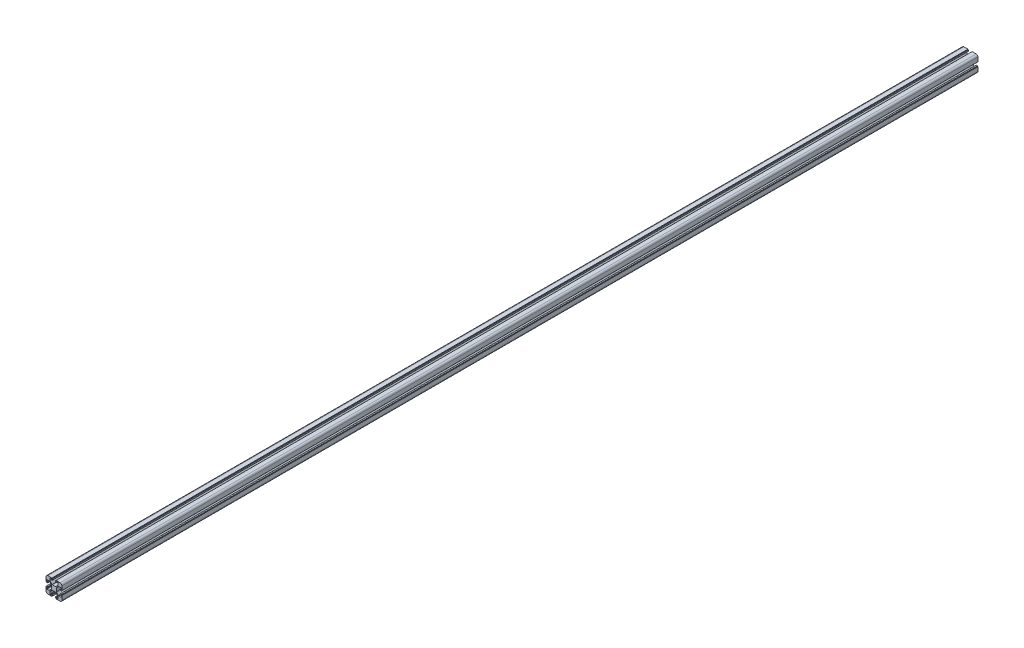
SolidWorks part; units mm, degrees
material "6063-T5"
ref_plane "Front Plane" through (0, 0, 0) normal (0, 0, 1) x (1, 0, 0)
ref_plane "Top Plane" through (0, 0, 0) normal (0, 1, 0) x (1, 0, 0)
ref_plane "Right Plane" through (0, 0, 0) normal (1, 0, 0) x (0, 0, -1)
sketch "Sketch2" plane through (0, 0, 0) normal (0, 0, 1) x (1, 0, 0)
  line L0 (4.5, 0) -> (14.7, 0)
  line L1 (40, 4.5) -> (40, 14.7)
  line L2 (35.5, 40) -> (25.3, 40)
  line L3 (0, 35.5) -> (0, 25.3)
  line L4 (15.9, 1.2) -> (15.9, 4.2)
  line L5 (24.1, 1.2) -> (24.1, 4.2)
  line L6 (38.8, 24.1) -> (35.8, 24.1)
  line L7 (35.5, 24.4) -> (35.5, 26.1)
  line L8 (14, 23.7574) -> (14, 16.2426)
  line L9 (16.2426, 14) -> (23.7574, 14)
  line L10 (26, 16.2426) -> (26, 23.7574)
  line L11 (13.4142, 14.8284) -> (8.9216, 10.3358)
  line L12 (23.7574, 26) -> (16.2426, 26)
  line L13 (4.5, 24.4) -> (4.5, 26.1)
  line L14 (1.2, 24.1) -> (4.2, 24.1)
  line L15 (15.9, 38.8) -> (15.9, 35.8)
  line L16 (14.8284, 26.5858) -> (10.3358, 31.0784)
  line L17 (13.4142, 25.1716) -> (8.9216, 29.6642)
  line L18 (14.8284, 13.4142) -> (10.3358, 8.9216)
  line L19 (25.1716, 13.4142) -> (29.6642, 8.9216)
  line L20 (26.5858, 14.8284) -> (31.0784, 10.3358)
  line L21 (26.5858, 25.1716) -> (31.0784, 29.6642)
  line L22 (25.1716, 26.5858) -> (29.6642, 31.0784)
  line L23 (24.1, 38.8) -> (24.1, 35.8)
  line L24 (14.7, 40) -> (4.5, 40)
  line L25 (25.3, 0) -> (35.5, 0)
  line L26 (38.8, 15.9) -> (35.8, 15.9)
  line L27 (40, 25.3) -> (40, 35.5)
  line L28 (1.2, 15.9) -> (4.2, 15.9)
  line L29 (0, 14.7) -> (0, 4.5)
  line L30 (4.5, 15.6) -> (4.5, 13.9)
  line L31 (35.5, 15.6) -> (35.5, 13.9)
  line L32 (15.6, 35.5) -> (13.9, 35.5)
  line L33 (24.4, 35.5) -> (26.1, 35.5)
  line L34 (15.6, 4.5) -> (13.9, 4.5)
  line L35 (24.4, 4.5) -> (26.1, 4.5)
  line L36 (12.6, 38.5) -> (10.75, 38.5)
  line L37 (1.5, 12.6) -> (1.5, 10.75)
  line L38 (27.4, 1.5) -> (29.25, 1.5)
  line L39 (38.5, 27.4) -> (38.5, 29.25)
  line L40 (38.5, 10.75) -> (38.5, 12.6)
  line L41 (29.25, 38.5) -> (27.4, 38.5)
  line L42 (1.5, 29.25) -> (1.5, 27.4)
  line L43 (10.75, 1.5) -> (12.6, 1.5)
  line L44 (35.8, 26.4) -> (37.5, 26.4)
  line L45 (35.8, 13.6) -> (37.5, 13.6)
  line L46 (4.2, 26.4) -> (2.5, 26.4)
  line L47 (13.6, 35.8) -> (13.6, 37.5)
  line L48 (26.4, 35.8) -> (26.4, 37.5)
  line L49 (4.2, 13.6) -> (2.5, 13.6)
  line L50 (13.6, 4.2) -> (13.6, 2.5)
  line L51 (26.4, 4.2) -> (26.4, 2.5)
  line L52 (9.75, 7.5074) -> (9.75, 2.5)
  line L53 (30.25, 7.5074) -> (30.25, 2.5)
  line L54 (9.75, 37.5) -> (9.75, 32.4926)
  line L55 (30.25, 37.5) -> (30.25, 32.4926)
  line L56 (32.4926, 30.25) -> (37.5, 30.25)
  line L57 (37.5, 9.75) -> (32.4926, 9.75)
  line L58 (2.5, 30.25) -> (7.5074, 30.25)
  line L59 (2.5, 9.75) -> (7.5074, 9.75)
  line L60 (31.55, 37.7) -> (31.55, 32.55)
  line L61 (32.55, 31.55) -> (37.7, 31.55)
  line L62 (1.3, 35.5) -> (1.3, 32.55)
  line L63 (4.5, 38.7) -> (7.45, 38.7)
  line L64 (32.55, 38.7) -> (35.5, 38.7)
  line L65 (38.7, 35.5) -> (38.7, 32.55)
  line L66 (8.45, 37.7) -> (8.45, 32.55)
  line L67 (2.3, 31.55) -> (7.45, 31.55)
  line L68 (1.3, 7.45) -> (1.3, 4.5)
  line L69 (2.3, 8.45) -> (7.45, 8.45)
  line L70 (8.45, 7.45) -> (8.45, 2.3)
  line L71 (4.5, 1.3) -> (7.45, 1.3)
  line L72 (31.55, 7.45) -> (31.55, 2.3)
  line L73 (32.55, 8.45) -> (37.7, 8.45)
  line L74 (38.7, 7.45) -> (38.7, 4.5)
  line L75 (32.55, 1.3) -> (35.5, 1.3)
  line L77 (14.9, 39.8) -> (14.9, 39.2)
  line L78 (15.1, 39) -> (15.7, 39)
  line L79 (25.1, 39.8) -> (25.1, 39.2)
  line L80 (24.9, 39) -> (24.3, 39)
  line L81 (25.1, 0.2) -> (25.1, 0.8)
  line L82 (24.9, 1) -> (24.3, 1)
  line L83 (14.9, 0.2) -> (14.9, 0.8)
  line L84 (15.1, 1) -> (15.7, 1)
  line L85 (0.2, 25.1) -> (0.8, 25.1)
  line L86 (1, 24.9) -> (1, 24.3)
  line L87 (0.2, 14.9) -> (0.8, 14.9)
  line L88 (1, 15.1) -> (1, 15.7)
  line L89 (39.8, 25.1) -> (39.2, 25.1)
  line L90 (39, 24.9) -> (39, 24.3)
  line L91 (39, 15.7) -> (39, 15.1)
  line L92 (39.2, 14.9) -> (39.8, 14.9)
  circle A0 centre (20, 20) radius 3.4
  arc A1 (1.3, 35.5) -> (4.5, 38.7) centre (4.5, 35.5) cw
  arc A2 (1.3, 4.5) -> (4.5, 1.3) centre (4.5, 4.5) ccw
  arc A3 (38.7, 4.5) -> (35.5, 1.3) centre (35.5, 4.5) cw
  arc A4 (35.5, 38.7) -> (38.7, 35.5) centre (35.5, 35.5) cw
  arc A5 (40, 35.5) -> (35.5, 40) centre (35.5, 35.5) ccw
  arc A6 (35.5, 0) -> (40, 4.5) centre (35.5, 4.5) ccw
  arc A7 (4.5, 0) -> (0, 4.5) centre (4.5, 4.5) cw
  arc A8 (4.5, 40) -> (0, 35.5) centre (4.5, 35.5) ccw
  arc A9 (13.4142, 14.8284) -> (14, 16.2426) centre (12, 16.2426) ccw
  arc A10 (7.5074, 9.75) -> (8.9216, 10.3358) centre (7.5074, 11.75) ccw
  arc A11 (9.75, 7.5074) -> (10.3358, 8.9216) centre (11.75, 7.5074) cw
  arc A12 (30.25, 7.5074) -> (29.6642, 8.9216) centre (28.25, 7.5074) ccw
  arc A13 (14.8284, 13.4142) -> (16.2426, 14) centre (16.2426, 12) cw
  arc A14 (25.1716, 13.4142) -> (23.7574, 14) centre (23.7574, 12) ccw
  arc A15 (32.4926, 9.75) -> (31.0784, 10.3358) centre (32.4926, 11.75) cw
  arc A16 (26.5858, 14.8284) -> (26, 16.2426) centre (28, 16.2426) cw
  arc A17 (32.4926, 30.25) -> (31.0784, 29.6642) centre (32.4926, 28.25) ccw
  arc A18 (26.5858, 25.1716) -> (26, 23.7574) centre (28, 23.7574) ccw
  arc A19 (13.4142, 25.1716) -> (14, 23.7574) centre (12, 23.7574) cw
  arc A20 (7.5074, 30.25) -> (8.9216, 29.6642) centre (7.5074, 28.25) cw
  arc A21 (9.75, 32.4926) -> (10.3358, 31.0784) centre (11.75, 32.4926) ccw
  arc A22 (30.25, 32.4926) -> (29.6642, 31.0784) centre (28.25, 32.4926) cw
  arc A23 (25.1716, 26.5858) -> (23.7574, 26) centre (23.7574, 28) cw
  arc A24 (14.8284, 26.5858) -> (16.2426, 26) centre (16.2426, 28) ccw
  arc A25 (37.7, 8.45) -> (38.7, 7.45) centre (37.7, 7.45) cw
  arc A26 (31.55, 2.3) -> (32.55, 1.3) centre (32.55, 2.3) ccw
  arc A27 (31.55, 7.45) -> (32.55, 8.45) centre (32.55, 7.45) cw
  arc A28 (8.45, 2.3) -> (7.45, 1.3) centre (7.45, 2.3) cw
  arc A29 (1.3, 7.45) -> (2.3, 8.45) centre (2.3, 7.45) cw
  arc A30 (7.45, 8.45) -> (8.45, 7.45) centre (7.45, 7.45) cw
  arc A31 (38.7, 32.55) -> (37.7, 31.55) centre (37.7, 32.55) cw
  arc A32 (31.55, 32.55) -> (32.55, 31.55) centre (32.55, 32.55) ccw
  arc A33 (31.55, 37.7) -> (32.55, 38.7) centre (32.55, 37.7) cw
  arc A34 (7.45, 38.7) -> (8.45, 37.7) centre (7.45, 37.7) cw
  arc A35 (8.45, 32.55) -> (7.45, 31.55) centre (7.45, 32.55) cw
  arc A36 (1.3, 32.55) -> (2.3, 31.55) centre (2.3, 32.55) ccw
  arc A37 (30.25, 2.5) -> (29.25, 1.5) centre (29.25, 2.5) cw
  arc A38 (26.4, 2.5) -> (27.4, 1.5) centre (27.4, 2.5) ccw
  arc A39 (13.6, 2.5) -> (12.6, 1.5) centre (12.6, 2.5) cw
  arc A40 (9.75, 2.5) -> (10.75, 1.5) centre (10.75, 2.5) ccw
  arc A41 (26.4, 37.5) -> (27.4, 38.5) centre (27.4, 37.5) cw
  arc A42 (30.25, 37.5) -> (29.25, 38.5) centre (29.25, 37.5) ccw
  arc A43 (37.5, 26.4) -> (38.5, 27.4) centre (37.5, 27.4) ccw
  arc A44 (37.5, 30.25) -> (38.5, 29.25) centre (37.5, 29.25) cw
  arc A45 (37.5, 13.6) -> (38.5, 12.6) centre (37.5, 12.6) cw
  arc A46 (37.5, 9.75) -> (38.5, 10.75) centre (37.5, 10.75) ccw
  arc A47 (2.5, 9.75) -> (1.5, 10.75) centre (2.5, 10.75) cw
  arc A48 (2.5, 13.6) -> (1.5, 12.6) centre (2.5, 12.6) ccw
  arc A49 (2.5, 26.4) -> (1.5, 27.4) centre (2.5, 27.4) cw
  arc A50 (2.5, 30.25) -> (1.5, 29.25) centre (2.5, 29.25) ccw
  arc A51 (9.75, 37.5) -> (10.75, 38.5) centre (10.75, 37.5) cw
  arc A52 (13.6, 37.5) -> (12.6, 38.5) centre (12.6, 37.5) ccw
  arc A53 (26.1, 35.5) -> (26.4, 35.8) centre (26.1, 35.8) ccw
  arc A54 (24.1, 35.8) -> (24.4, 35.5) centre (24.4, 35.8) ccw
  arc A55 (15.9, 35.8) -> (15.6, 35.5) centre (15.6, 35.8) cw
  arc A56 (13.9, 35.5) -> (13.6, 35.8) centre (13.9, 35.8) cw
  arc A57 (13.9, 4.5) -> (13.6, 4.2) centre (13.9, 4.2) ccw
  arc A58 (15.9, 4.2) -> (15.6, 4.5) centre (15.6, 4.2) ccw
  arc A59 (24.1, 4.2) -> (24.4, 4.5) centre (24.4, 4.2) cw
  arc A60 (26.1, 4.5) -> (26.4, 4.2) centre (26.1, 4.2) cw
  arc A61 (35.5, 13.9) -> (35.8, 13.6) centre (35.8, 13.9) ccw
  arc A62 (35.8, 15.9) -> (35.5, 15.6) centre (35.8, 15.6) ccw
  arc A63 (35.8, 24.1) -> (35.5, 24.4) centre (35.8, 24.4) cw
  arc A64 (35.5, 26.1) -> (35.8, 26.4) centre (35.8, 26.1) cw
  arc A65 (4.5, 13.9) -> (4.2, 13.6) centre (4.2, 13.9) cw
  arc A66 (4.2, 15.9) -> (4.5, 15.6) centre (4.2, 15.6) cw
  arc A67 (4.2, 24.1) -> (4.5, 24.4) centre (4.2, 24.4) ccw
  arc A68 (4.5, 26.1) -> (4.2, 26.4) centre (4.2, 26.1) ccw
  arc A69 (25.3, 0) -> (25.1, 0.2) centre (25.3, 0.2) cw
  arc A70 (25.1, 0.8) -> (24.9, 1) centre (24.9, 0.8) ccw
  arc A71 (24.3, 1) -> (24.1, 1.2) centre (24.3, 1.2) cw
  arc A72 (14.7, 0) -> (14.9, 0.2) centre (14.7, 0.2) ccw
  arc A73 (14.9, 0.8) -> (15.1, 1) centre (15.1, 0.8) cw
  arc A74 (15.7, 1) -> (15.9, 1.2) centre (15.7, 1.2) ccw
  arc A75 (39.8, 14.9) -> (40, 14.7) centre (39.8, 14.7) cw
  arc A76 (39, 15.1) -> (39.2, 14.9) centre (39.2, 15.1) ccw
  arc A77 (38.8, 15.9) -> (39, 15.7) centre (38.8, 15.7) cw
  arc A78 (0, 25.3) -> (0.2, 25.1) centre (0.2, 25.3) ccw
  arc A79 (0.8, 25.1) -> (1, 24.9) centre (0.8, 24.9) cw
  arc A80 (1, 24.3) -> (1.2, 24.1) centre (1.2, 24.3) ccw
  arc A81 (0, 14.7) -> (0.2, 14.9) centre (0.2, 14.7) cw
  arc A82 (0.8, 14.9) -> (1, 15.1) centre (0.8, 15.1) ccw
  arc A83 (1, 15.7) -> (1.2, 15.9) centre (1.2, 15.7) cw
  arc A84 (39, 24.3) -> (38.8, 24.1) centre (38.8, 24.3) cw
  arc A85 (39.2, 25.1) -> (39, 24.9) centre (39.2, 24.9) ccw
  arc A86 (40, 25.3) -> (39.8, 25.1) centre (39.8, 25.3) cw
  arc A87 (24.3, 39) -> (24.1, 38.8) centre (24.3, 38.8) ccw
  arc A88 (25.1, 39.2) -> (24.9, 39) centre (24.9, 39.2) cw
  arc A89 (25.3, 40) -> (25.1, 39.8) centre (25.3, 39.8) ccw
  arc A90 (14.9, 39.2) -> (15.1, 39) centre (15.1, 39.2) ccw
  arc A91 (15.7, 39) -> (15.9, 38.8) centre (15.7, 38.8) cw
  arc A92 (14.7, 40) -> (14.9, 39.8) centre (14.7, 39.8) cw
  point P93 (0, 0)
extrude "Boss-Extrude1" add sketch "Sketch2" along normal blind 50
sketch "Sketch3" plane through (0, 0, 50) normal (0, 0, 1) x (1, 0, 0)
  line L76 (25.3, 0) -> (35.5, 0)
  line L77 (40, 4.5) -> (40, 14.7)
  line L78 (39.8, 14.9) -> (39.2, 14.9)
  line L79 (39, 15.1) -> (39, 15.7)
  line L80 (38.8, 15.9) -> (35.8, 15.9)
  line L81 (35.5, 15.6) -> (35.5, 13.9)
  line L82 (35.8, 13.6) -> (37.5, 13.6)
  line L83 (38.5, 12.6) -> (38.5, 10.75)
  line L84 (37.5, 9.75) -> (32.4926, 9.75)
  line L85 (31.0784, 10.3358) -> (26.5858, 14.8284)
  line L86 (26, 16.2426) -> (26, 23.7574)
  line L87 (26.5858, 25.1716) -> (31.0784, 29.6642)
  line L88 (32.4926, 30.25) -> (37.5, 30.25)
  line L89 (38.5, 29.25) -> (38.5, 27.4)
  line L90 (37.5, 26.4) -> (35.8, 26.4)
  line L91 (35.5, 26.1) -> (35.5, 24.4)
  line L92 (35.8, 24.1) -> (38.8, 24.1)
  line L93 (39, 24.3) -> (39, 24.9)
  line L94 (39.2, 25.1) -> (39.8, 25.1)
  line L95 (40, 25.3) -> (40, 35.5)
  line L96 (35.5, 40) -> (25.3, 40)
  line L97 (25.1, 39.8) -> (25.1, 39.2)
  line L98 (24.9, 39) -> (24.3, 39)
  line L99 (24.1, 38.8) -> (24.1, 35.8)
  line L100 (24.4, 35.5) -> (26.1, 35.5)
  line L101 (26.4, 35.8) -> (26.4, 37.5)
  line L102 (27.4, 38.5) -> (29.25, 38.5)
  line L103 (30.25, 37.5) -> (30.25, 32.4926)
  line L104 (29.6642, 31.0784) -> (25.1716, 26.5858)
  line L105 (23.7574, 26) -> (16.2426, 26)
  line L106 (14.8284, 26.5858) -> (10.3358, 31.0784)
  line L107 (9.75, 32.4926) -> (9.75, 37.5)
  line L108 (10.75, 38.5) -> (12.6, 38.5)
  line L109 (13.6, 37.5) -> (13.6, 35.8)
  line L110 (13.9, 35.5) -> (15.6, 35.5)
  line L111 (15.9, 35.8) -> (15.9, 38.8)
  line L112 (15.7, 39) -> (15.1, 39)
  line L113 (14.9, 39.2) -> (14.9, 39.8)
  line L114 (14.7, 40) -> (4.5, 40)
  line L115 (0, 35.5) -> (0, 25.3)
  line L116 (0.2, 25.1) -> (0.8, 25.1)
  line L117 (1, 24.9) -> (1, 24.3)
  line L118 (1.2, 24.1) -> (4.2, 24.1)
  line L119 (4.5, 24.4) -> (4.5, 26.1)
  line L120 (4.2, 26.4) -> (2.5, 26.4)
  line L121 (1.5, 27.4) -> (1.5, 29.25)
  line L122 (2.5, 30.25) -> (7.5074, 30.25)
  line L123 (8.9216, 29.6642) -> (13.4142, 25.1716)
  line L124 (14, 23.7574) -> (14, 16.2426)
  line L125 (13.4142, 14.8284) -> (8.9216, 10.3358)
  line L126 (7.5074, 9.75) -> (2.5, 9.75)
  line L127 (1.5, 10.75) -> (1.5, 12.6)
  line L128 (2.5, 13.6) -> (4.2, 13.6)
  line L129 (4.5, 13.9) -> (4.5, 15.6)
  line L130 (4.2, 15.9) -> (1.2, 15.9)
  line L131 (1, 15.7) -> (1, 15.1)
  line L132 (0.8, 14.9) -> (0.2, 14.9)
  line L133 (0, 14.7) -> (0, 4.5)
  line L134 (4.5, 0) -> (14.7, 0)
  line L135 (14.9, 0.2) -> (14.9, 0.8)
  line L136 (15.1, 1) -> (15.7, 1)
  line L137 (15.9, 1.2) -> (15.9, 4.2)
  line L138 (15.6, 4.5) -> (13.9, 4.5)
  line L139 (13.6, 4.2) -> (13.6, 2.5)
  line L140 (12.6, 1.5) -> (10.75, 1.5)
  line L141 (9.75, 2.5) -> (9.75, 7.5074)
  line L142 (10.3358, 8.9216) -> (14.8284, 13.4142)
  line L143 (16.2426, 14) -> (23.7574, 14)
  line L144 (25.1716, 13.4142) -> (29.6642, 8.9216)
  line L145 (30.25, 7.5074) -> (30.25, 2.5)
  line L146 (29.25, 1.5) -> (27.4, 1.5)
  line L147 (26.4, 2.5) -> (26.4, 4.2)
  line L148 (26.1, 4.5) -> (24.4, 4.5)
  line L149 (24.1, 4.2) -> (24.1, 1.2)
  line L150 (24.3, 1) -> (24.9, 1)
  line L151 (25.1, 0.8) -> (25.1, 0.2)
  line L152 (25.3, 0) -> (35.5, 0)
  line L153 (40, 4.5) -> (40, 14.7)
  line L154 (39.8, 14.9) -> (39.2, 14.9)
  line L155 (39, 15.1) -> (39, 15.7)
  line L156 (38.8, 15.9) -> (35.8, 15.9)
  line L157 (35.5, 15.6) -> (35.5, 13.9)
  line L158 (35.8, 13.6) -> (37.5, 13.6)
  line L159 (38.5, 12.6) -> (38.5, 10.75)
  line L160 (37.5, 9.75) -> (32.4926, 9.75)
  line L161 (31.0784, 10.3358) -> (26.5858, 14.8284)
  line L162 (26, 16.2426) -> (26, 23.7574)
  line L163 (26.5858, 25.1716) -> (31.0784, 29.6642)
  line L164 (32.4926, 30.25) -> (37.5, 30.25)
  line L165 (38.5, 29.25) -> (38.5, 27.4)
  line L166 (37.5, 26.4) -> (35.8, 26.4)
  line L167 (35.5, 26.1) -> (35.5, 24.4)
  line L168 (35.8, 24.1) -> (38.8, 24.1)
  line L169 (39, 24.3) -> (39, 24.9)
  line L170 (39.2, 25.1) -> (39.8, 25.1)
  line L171 (40, 25.3) -> (40, 35.5)
  line L172 (35.5, 40) -> (25.3, 40)
  line L173 (25.1, 39.8) -> (25.1, 39.2)
  line L174 (24.9, 39) -> (24.3, 39)
  line L175 (24.1, 38.8) -> (24.1, 35.8)
  line L176 (24.4, 35.5) -> (26.1, 35.5)
  line L177 (26.4, 35.8) -> (26.4, 37.5)
  line L178 (27.4, 38.5) -> (29.25, 38.5)
  line L179 (30.25, 37.5) -> (30.25, 32.4926)
  line L180 (29.6642, 31.0784) -> (25.1716, 26.5858)
  line L181 (23.7574, 26) -> (16.2426, 26)
  line L182 (14.8284, 26.5858) -> (10.3358, 31.0784)
  line L183 (9.75, 32.4926) -> (9.75, 37.5)
  line L184 (10.75, 38.5) -> (12.6, 38.5)
  line L185 (13.6, 37.5) -> (13.6, 35.8)
  line L186 (13.9, 35.5) -> (15.6, 35.5)
  line L187 (15.9, 35.8) -> (15.9, 38.8)
  line L188 (15.7, 39) -> (15.1, 39)
  line L189 (14.9, 39.2) -> (14.9, 39.8)
  line L190 (14.7, 40) -> (4.5, 40)
  line L191 (0, 35.5) -> (0, 25.3)
  line L192 (0.2, 25.1) -> (0.8, 25.1)
  line L193 (1, 24.9) -> (1, 24.3)
  line L194 (1.2, 24.1) -> (4.2, 24.1)
  line L195 (4.5, 24.4) -> (4.5, 26.1)
  line L196 (4.2, 26.4) -> (2.5, 26.4)
  line L197 (1.5, 27.4) -> (1.5, 29.25)
  line L198 (2.5, 30.25) -> (7.5074, 30.25)
  line L199 (8.9216, 29.6642) -> (13.4142, 25.1716)
  line L200 (14, 23.7574) -> (14, 16.2426)
  line L201 (13.4142, 14.8284) -> (8.9216, 10.3358)
  line L202 (7.5074, 9.75) -> (2.5, 9.75)
  line L203 (1.5, 10.75) -> (1.5, 12.6)
  line L204 (2.5, 13.6) -> (4.2, 13.6)
  line L205 (4.5, 13.9) -> (4.5, 15.6)
  line L206 (4.2, 15.9) -> (1.2, 15.9)
  line L207 (1, 15.7) -> (1, 15.1)
  line L208 (0.8, 14.9) -> (0.2, 14.9)
  line L209 (0, 14.7) -> (0, 4.5)
  line L210 (4.5, 0) -> (14.7, 0)
  line L211 (14.9, 0.2) -> (14.9, 0.8)
  line L212 (15.1, 1) -> (15.7, 1)
  line L213 (15.9, 1.2) -> (15.9, 4.2)
  line L214 (15.6, 4.5) -> (13.9, 4.5)
  line L215 (13.6, 4.2) -> (13.6, 2.5)
  line L216 (12.6, 1.5) -> (10.75, 1.5)
  line L217 (9.75, 2.5) -> (9.75, 7.5074)
  line L218 (10.3358, 8.9216) -> (14.8284, 13.4142)
  line L219 (16.2426, 14) -> (23.7574, 14)
  line L220 (25.1716, 13.4142) -> (29.6642, 8.9216)
  line L221 (30.25, 7.5074) -> (30.25, 2.5)
  line L222 (29.25, 1.5) -> (27.4, 1.5)
  line L223 (26.4, 2.5) -> (26.4, 4.2)
  line L224 (26.1, 4.5) -> (24.4, 4.5)
  line L225 (24.1, 4.2) -> (24.1, 1.2)
  line L226 (24.3, 1) -> (24.9, 1)
  line L227 (25.1, 0.8) -> (25.1, 0.2)
  arc A76 (25.1, 0.2) -> (25.3, 0) centre (25.3, 0.2) ccw
  arc A77 (35.5, 0) -> (40, 4.5) centre (35.5, 4.5) ccw
  arc A78 (40, 14.7) -> (39.8, 14.9) centre (39.8, 14.7) ccw
  arc A79 (39, 15.1) -> (39.2, 14.9) centre (39.2, 15.1) ccw
  arc A80 (39, 15.7) -> (38.8, 15.9) centre (38.8, 15.7) ccw
  arc A81 (35.8, 15.9) -> (35.5, 15.6) centre (35.8, 15.6) ccw
  arc A82 (35.5, 13.9) -> (35.8, 13.6) centre (35.8, 13.9) ccw
  arc A83 (38.5, 12.6) -> (37.5, 13.6) centre (37.5, 12.6) ccw
  arc A84 (37.5, 9.75) -> (38.5, 10.75) centre (37.5, 10.75) ccw
  arc A85 (31.0784, 10.3358) -> (32.4926, 9.75) centre (32.4926, 11.75) ccw
  arc A86 (26, 16.2426) -> (26.5858, 14.8284) centre (28, 16.2426) ccw
  arc A87 (26.5858, 25.1716) -> (26, 23.7574) centre (28, 23.7574) ccw
  arc A88 (32.4926, 30.25) -> (31.0784, 29.6642) centre (32.4926, 28.25) ccw
  arc A89 (38.5, 29.25) -> (37.5, 30.25) centre (37.5, 29.25) ccw
  arc A90 (37.5, 26.4) -> (38.5, 27.4) centre (37.5, 27.4) ccw
  arc A91 (35.8, 26.4) -> (35.5, 26.1) centre (35.8, 26.1) ccw
  arc A92 (35.5, 24.4) -> (35.8, 24.1) centre (35.8, 24.4) ccw
  arc A93 (38.8, 24.1) -> (39, 24.3) centre (38.8, 24.3) ccw
  arc A94 (39.2, 25.1) -> (39, 24.9) centre (39.2, 24.9) ccw
  arc A95 (39.8, 25.1) -> (40, 25.3) centre (39.8, 25.3) ccw
  arc A96 (40, 35.5) -> (35.5, 40) centre (35.5, 35.5) ccw
  arc A97 (25.3, 40) -> (25.1, 39.8) centre (25.3, 39.8) ccw
  arc A98 (24.9, 39) -> (25.1, 39.2) centre (24.9, 39.2) ccw
  arc A99 (24.3, 39) -> (24.1, 38.8) centre (24.3, 38.8) ccw
  arc A100 (24.1, 35.8) -> (24.4, 35.5) centre (24.4, 35.8) ccw
  arc A101 (26.1, 35.5) -> (26.4, 35.8) centre (26.1, 35.8) ccw
  arc A102 (27.4, 38.5) -> (26.4, 37.5) centre (27.4, 37.5) ccw
  arc A103 (30.25, 37.5) -> (29.25, 38.5) centre (29.25, 37.5) ccw
  arc A104 (29.6642, 31.0784) -> (30.25, 32.4926) centre (28.25, 32.4926) ccw
  arc A105 (23.7574, 26) -> (25.1716, 26.5858) centre (23.7574, 28) ccw
  arc A106 (14.8284, 26.5858) -> (16.2426, 26) centre (16.2426, 28) ccw
  arc A107 (9.75, 32.4926) -> (10.3358, 31.0784) centre (11.75, 32.4926) ccw
  arc A108 (10.75, 38.5) -> (9.75, 37.5) centre (10.75, 37.5) ccw
  arc A109 (13.6, 37.5) -> (12.6, 38.5) centre (12.6, 37.5) ccw
  arc A110 (13.6, 35.8) -> (13.9, 35.5) centre (13.9, 35.8) ccw
  arc A111 (15.6, 35.5) -> (15.9, 35.8) centre (15.6, 35.8) ccw
  arc A112 (15.9, 38.8) -> (15.7, 39) centre (15.7, 38.8) ccw
  arc A113 (14.9, 39.2) -> (15.1, 39) centre (15.1, 39.2) ccw
  arc A114 (14.9, 39.8) -> (14.7, 40) centre (14.7, 39.8) ccw
  arc A115 (4.5, 40) -> (0, 35.5) centre (4.5, 35.5) ccw
  arc A116 (0, 25.3) -> (0.2, 25.1) centre (0.2, 25.3) ccw
  arc A117 (1, 24.9) -> (0.8, 25.1) centre (0.8, 24.9) ccw
  arc A118 (1, 24.3) -> (1.2, 24.1) centre (1.2, 24.3) ccw
  arc A119 (4.2, 24.1) -> (4.5, 24.4) centre (4.2, 24.4) ccw
  arc A120 (4.5, 26.1) -> (4.2, 26.4) centre (4.2, 26.1) ccw
  arc A121 (1.5, 27.4) -> (2.5, 26.4) centre (2.5, 27.4) ccw
  arc A122 (2.5, 30.25) -> (1.5, 29.25) centre (2.5, 29.25) ccw
  arc A123 (8.9216, 29.6642) -> (7.5074, 30.25) centre (7.5074, 28.25) ccw
  arc A124 (14, 23.7574) -> (13.4142, 25.1716) centre (12, 23.7574) ccw
  arc A125 (13.4142, 14.8284) -> (14, 16.2426) centre (12, 16.2426) ccw
  arc A126 (7.5074, 9.75) -> (8.9216, 10.3358) centre (7.5074, 11.75) ccw
  arc A127 (1.5, 10.75) -> (2.5, 9.75) centre (2.5, 10.75) ccw
  arc A128 (2.5, 13.6) -> (1.5, 12.6) centre (2.5, 12.6) ccw
  arc A129 (4.2, 13.6) -> (4.5, 13.9) centre (4.2, 13.9) ccw
  arc A130 (4.5, 15.6) -> (4.2, 15.9) centre (4.2, 15.6) ccw
  arc A131 (1.2, 15.9) -> (1, 15.7) centre (1.2, 15.7) ccw
  arc A132 (0.8, 14.9) -> (1, 15.1) centre (0.8, 15.1) ccw
  arc A133 (0.2, 14.9) -> (0, 14.7) centre (0.2, 14.7) ccw
  arc A134 (0, 4.5) -> (4.5, 0) centre (4.5, 4.5) ccw
  arc A135 (14.7, 0) -> (14.9, 0.2) centre (14.7, 0.2) ccw
  arc A136 (15.1, 1) -> (14.9, 0.8) centre (15.1, 0.8) ccw
  arc A137 (15.7, 1) -> (15.9, 1.2) centre (15.7, 1.2) ccw
  arc A138 (15.9, 4.2) -> (15.6, 4.5) centre (15.6, 4.2) ccw
  arc A139 (13.9, 4.5) -> (13.6, 4.2) centre (13.9, 4.2) ccw
  arc A140 (12.6, 1.5) -> (13.6, 2.5) centre (12.6, 2.5) ccw
  arc A141 (9.75, 2.5) -> (10.75, 1.5) centre (10.75, 2.5) ccw
  arc A142 (10.3358, 8.9216) -> (9.75, 7.5074) centre (11.75, 7.5074) ccw
  arc A143 (16.2426, 14) -> (14.8284, 13.4142) centre (16.2426, 12) ccw
  arc A144 (25.1716, 13.4142) -> (23.7574, 14) centre (23.7574, 12) ccw
  arc A145 (30.25, 7.5074) -> (29.6642, 8.9216) centre (28.25, 7.5074) ccw
  arc A146 (29.25, 1.5) -> (30.25, 2.5) centre (29.25, 2.5) ccw
  arc A147 (26.4, 2.5) -> (27.4, 1.5) centre (27.4, 2.5) ccw
  arc A148 (26.4, 4.2) -> (26.1, 4.5) centre (26.1, 4.2) ccw
  arc A149 (24.4, 4.5) -> (24.1, 4.2) centre (24.4, 4.2) ccw
  arc A150 (24.1, 1.2) -> (24.3, 1) centre (24.3, 1.2) ccw
  arc A151 (25.1, 0.8) -> (24.9, 1) centre (24.9, 0.8) ccw
  arc A152 (25.1, 0.2) -> (25.3, 0) centre (25.3, 0.2) ccw
  arc A153 (35.5, 0) -> (40, 4.5) centre (35.5, 4.5) ccw
  arc A154 (40, 14.7) -> (39.8, 14.9) centre (39.8, 14.7) ccw
  arc A155 (39, 15.1) -> (39.2, 14.9) centre (39.2, 15.1) ccw
  arc A156 (39, 15.7) -> (38.8, 15.9) centre (38.8, 15.7) ccw
  arc A157 (35.8, 15.9) -> (35.5, 15.6) centre (35.8, 15.6) ccw
  arc A158 (35.5, 13.9) -> (35.8, 13.6) centre (35.8, 13.9) ccw
  arc A159 (38.5, 12.6) -> (37.5, 13.6) centre (37.5, 12.6) ccw
  arc A160 (37.5, 9.75) -> (38.5, 10.75) centre (37.5, 10.75) ccw
  arc A161 (31.0784, 10.3358) -> (32.4926, 9.75) centre (32.4926, 11.75) ccw
  arc A162 (26, 16.2426) -> (26.5858, 14.8284) centre (28, 16.2426) ccw
  arc A163 (26.5858, 25.1716) -> (26, 23.7574) centre (28, 23.7574) ccw
  arc A164 (32.4926, 30.25) -> (31.0784, 29.6642) centre (32.4926, 28.25) ccw
  arc A165 (38.5, 29.25) -> (37.5, 30.25) centre (37.5, 29.25) ccw
  arc A166 (37.5, 26.4) -> (38.5, 27.4) centre (37.5, 27.4) ccw
  arc A167 (35.8, 26.4) -> (35.5, 26.1) centre (35.8, 26.1) ccw
  arc A168 (35.5, 24.4) -> (35.8, 24.1) centre (35.8, 24.4) ccw
  arc A169 (38.8, 24.1) -> (39, 24.3) centre (38.8, 24.3) ccw
  arc A170 (39.2, 25.1) -> (39, 24.9) centre (39.2, 24.9) ccw
  arc A171 (39.8, 25.1) -> (40, 25.3) centre (39.8, 25.3) ccw
  arc A172 (40, 35.5) -> (35.5, 40) centre (35.5, 35.5) ccw
  arc A173 (25.3, 40) -> (25.1, 39.8) centre (25.3, 39.8) ccw
  arc A174 (24.9, 39) -> (25.1, 39.2) centre (24.9, 39.2) ccw
  arc A175 (24.3, 39) -> (24.1, 38.8) centre (24.3, 38.8) ccw
  arc A176 (24.1, 35.8) -> (24.4, 35.5) centre (24.4, 35.8) ccw
  arc A177 (26.1, 35.5) -> (26.4, 35.8) centre (26.1, 35.8) ccw
  arc A178 (27.4, 38.5) -> (26.4, 37.5) centre (27.4, 37.5) ccw
  arc A179 (30.25, 37.5) -> (29.25, 38.5) centre (29.25, 37.5) ccw
  arc A180 (29.6642, 31.0784) -> (30.25, 32.4926) centre (28.25, 32.4926) ccw
  arc A181 (23.7574, 26) -> (25.1716, 26.5858) centre (23.7574, 28) ccw
  arc A182 (14.8284, 26.5858) -> (16.2426, 26) centre (16.2426, 28) ccw
  arc A183 (9.75, 32.4926) -> (10.3358, 31.0784) centre (11.75, 32.4926) ccw
  arc A184 (10.75, 38.5) -> (9.75, 37.5) centre (10.75, 37.5) ccw
  arc A185 (13.6, 37.5) -> (12.6, 38.5) centre (12.6, 37.5) ccw
  arc A186 (13.6, 35.8) -> (13.9, 35.5) centre (13.9, 35.8) ccw
  arc A187 (15.6, 35.5) -> (15.9, 35.8) centre (15.6, 35.8) ccw
  arc A188 (15.9, 38.8) -> (15.7, 39) centre (15.7, 38.8) ccw
  arc A189 (14.9, 39.2) -> (15.1, 39) centre (15.1, 39.2) ccw
  arc A190 (14.9, 39.8) -> (14.7, 40) centre (14.7, 39.8) ccw
  arc A191 (4.5, 40) -> (0, 35.5) centre (4.5, 35.5) ccw
  arc A192 (0, 25.3) -> (0.2, 25.1) centre (0.2, 25.3) ccw
  arc A193 (1, 24.9) -> (0.8, 25.1) centre (0.8, 24.9) ccw
  arc A194 (1, 24.3) -> (1.2, 24.1) centre (1.2, 24.3) ccw
  arc A195 (4.2, 24.1) -> (4.5, 24.4) centre (4.2, 24.4) ccw
  arc A196 (4.5, 26.1) -> (4.2, 26.4) centre (4.2, 26.1) ccw
  arc A197 (1.5, 27.4) -> (2.5, 26.4) centre (2.5, 27.4) ccw
  arc A198 (2.5, 30.25) -> (1.5, 29.25) centre (2.5, 29.25) ccw
  arc A199 (8.9216, 29.6642) -> (7.5074, 30.25) centre (7.5074, 28.25) ccw
  arc A200 (14, 23.7574) -> (13.4142, 25.1716) centre (12, 23.7574) ccw
  arc A201 (13.4142, 14.8284) -> (14, 16.2426) centre (12, 16.2426) ccw
  arc A202 (7.5074, 9.75) -> (8.9216, 10.3358) centre (7.5074, 11.75) ccw
  arc A203 (1.5, 10.75) -> (2.5, 9.75) centre (2.5, 10.75) ccw
  arc A204 (2.5, 13.6) -> (1.5, 12.6) centre (2.5, 12.6) ccw
  arc A205 (4.2, 13.6) -> (4.5, 13.9) centre (4.2, 13.9) ccw
  arc A206 (4.5, 15.6) -> (4.2, 15.9) centre (4.2, 15.6) ccw
  arc A207 (1.2, 15.9) -> (1, 15.7) centre (1.2, 15.7) ccw
  arc A208 (0.8, 14.9) -> (1, 15.1) centre (0.8, 15.1) ccw
  arc A209 (0.2, 14.9) -> (0, 14.7) centre (0.2, 14.7) ccw
  arc A210 (0, 4.5) -> (4.5, 0) centre (4.5, 4.5) ccw
  arc A211 (14.7, 0) -> (14.9, 0.2) centre (14.7, 0.2) ccw
  arc A212 (15.1, 1) -> (14.9, 0.8) centre (15.1, 0.8) ccw
  arc A213 (15.7, 1) -> (15.9, 1.2) centre (15.7, 1.2) ccw
  arc A214 (15.9, 4.2) -> (15.6, 4.5) centre (15.6, 4.2) ccw
  arc A215 (13.9, 4.5) -> (13.6, 4.2) centre (13.9, 4.2) ccw
  arc A216 (12.6, 1.5) -> (13.6, 2.5) centre (12.6, 2.5) ccw
  arc A217 (9.75, 2.5) -> (10.75, 1.5) centre (10.75, 2.5) ccw
  arc A218 (10.3358, 8.9216) -> (9.75, 7.5074) centre (11.75, 7.5074) ccw
  arc A219 (16.2426, 14) -> (14.8284, 13.4142) centre (16.2426, 12) ccw
  arc A220 (25.1716, 13.4142) -> (23.7574, 14) centre (23.7574, 12) ccw
  arc A221 (30.25, 7.5074) -> (29.6642, 8.9216) centre (28.25, 7.5074) ccw
  arc A222 (29.25, 1.5) -> (30.25, 2.5) centre (29.25, 2.5) ccw
  arc A223 (26.4, 2.5) -> (27.4, 1.5) centre (27.4, 2.5) ccw
  arc A224 (26.4, 4.2) -> (26.1, 4.5) centre (26.1, 4.2) ccw
  arc A225 (24.4, 4.5) -> (24.1, 4.2) centre (24.4, 4.2) ccw
  arc A226 (24.1, 1.2) -> (24.3, 1) centre (24.3, 1.2) ccw
  arc A227 (25.1, 0.8) -> (24.9, 1) centre (24.9, 0.8) ccw
  dimension "D1" = 0
extrude "Boss-Extrude2" add sketch "Sketch3" along normal blind 2250
